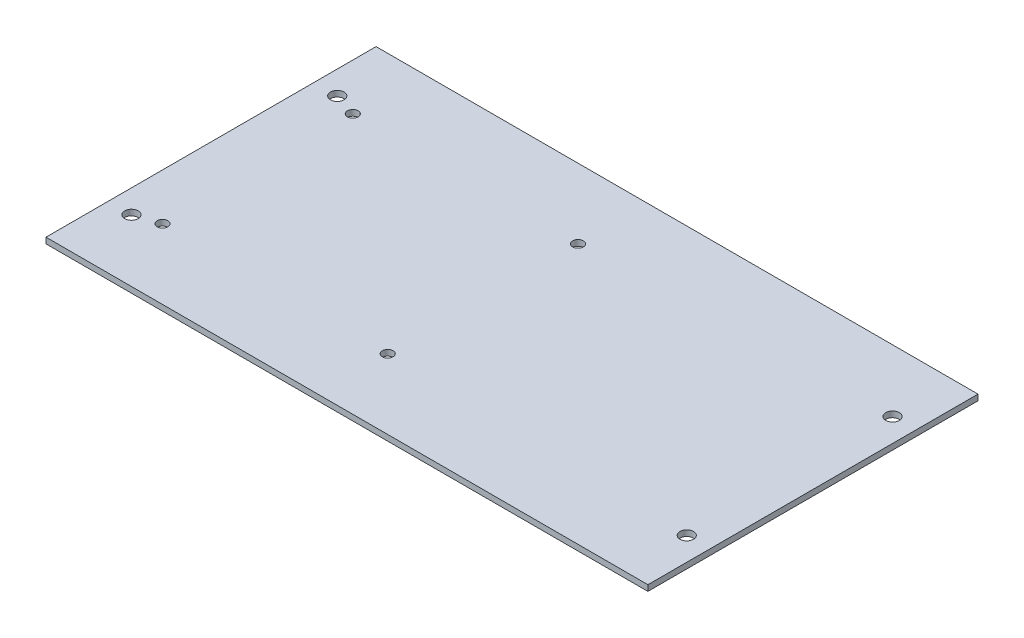
SolidWorks part; units mm, degrees
ref_plane "Спереди" through (0, 0, 0) normal (0, 0, 1) x (1, 0, 0)
ref_plane "Сверху" through (0, 0, 0) normal (0, 1, 0) x (1, 0, 0)
ref_plane "Справа" through (0, 0, 0) normal (1, 0, 0) x (0, 0, -1)
sketch "Эскиз1" plane through (0, 0, 0) normal (0, 1, 0) x (1, 0, 0)
  line L1 (77.5, -42.5) -> (-77.5, -42.5)
  line L2 (77.5, -42.5) -> (77.5, 42.5)
  line L3 (77.5, 42.5) -> (-77.5, 42.5)
  line L4 (-77.5, -42.5) -> (-77.5, 42.5)
  line L5 (77.5, -42.5) -> (-77.5, 42.5) construction
  line L6 (77.5, 42.5) -> (-77.5, -42.5) construction
  point P0 (0, 0)
  dimension "D1" = 155
  dimension "D2" = 85
extrude "Бобышка-Вытянуть1" add sketch "Эскиз1" along normal blind 1.5
sketch "Эскиз2" plane through (0, 1.5, 0) normal (0, 1, 0) x (1, 0, 0)
  line L0 (-77.5, 42.5) -> (-77.5, -42.5) construction
  line L1 (77.5, 42.5) -> (-77.5, 42.5) construction
  line L2 (-77.5, -42.5) -> (77.5, -42.5) construction
  line L3 (77.5, -42.5) -> (77.5, 42.5) construction
  circle A0 centre (-71.5, 26.5) radius 1.75
  circle A1 centre (-71.5, -26.5) radius 1.75
  circle A2 centre (71.5, -26.5) radius 1.75
  circle A3 centre (71.5, 26.5) radius 1.75
  dimension "D3" = 3.5
  dimension "D6" = 3.5
  dimension "D9" = 3.5
  dimension "D12" = 3.5
  dimension "D1" = 6
  dimension "D2" = 16
  dimension "D4" = 6
  dimension "D5" = 16
  dimension "D7" = 16
  dimension "D8" = 6
  dimension "D10" = 6
  dimension "D11" = 16
extrude "Вырез-Вытянуть1" cut sketch "Эскиз2" against normal through all
sketch "Эскиз3" plane through (0, 1.5, 0) normal (0, 1, 0) x (1, 0, 0)
  line L0 (77.5, 42.5) -> (-77.5, 42.5) construction
  line L1 (-77.5, 42.5) -> (-77.5, -42.5) construction
  line L2 (-77.5, -42.5) -> (77.5, -42.5) construction
  circle A0 centre (-65.5, 24.5) radius 1.375
  circle A1 centre (-65.5, -24.5) radius 1.375
  circle A2 centre (-7.5, 24.5) radius 1.375
  circle A3 centre (-7.5, -24.5) radius 1.375
  dimension "D3" = 2.75
  dimension "D4" = 12
  dimension "D6" = 2.75
  dimension "D12" = 2.75
  dimension "D13" = 2.75
  dimension "D1" = 18
  dimension "D2" = 12
  dimension "D5" = 18
  dimension "D7" = 49
  dimension "D8" = 58
  dimension "D9" = 58
  dimension "D10" = 18
  dimension "D11" = 18
extrude "Вырез-Вытянуть2" cut sketch "Эскиз3" against normal blind 10
